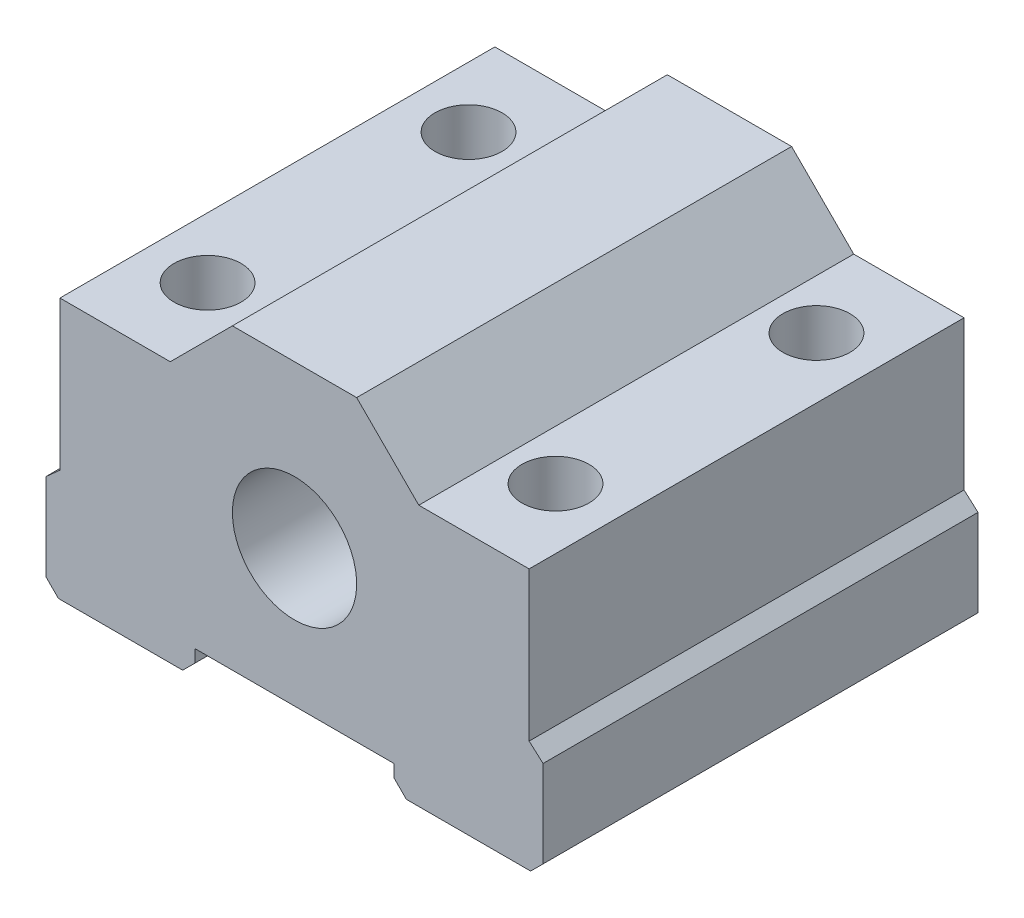
SolidWorks part; units mm, degrees
ref_plane "Спереди" through (0, 0, 0) normal (0, 0, 1) x (1, 0, 0)
ref_plane "Сверху" through (0, 0, 0) normal (0, 1, 0) x (1, 0, 0)
ref_plane "Справа" through (0, 0, 0) normal (1, 0, 0) x (0, 0, -1)
sketch "Эскиз1" plane through (0, 0, 0) normal (0, 0, 1) x (1, 0, 0)
  line L1 (-20, 13) -> (20, 13)
  line L2 (-20, 13) -> (-20, -13)
  line L3 (-20, -13) -> (20, -13)
  line L4 (20, 13) -> (20, -13)
  line L5 (-20, 13) -> (20, -13) construction
  line L6 (-20, -13) -> (20, 13) construction
  point P0 (0, 0)
  dimension "D1" = 26
  dimension "D2" = 40
extrude "Бобышка-Вытянуть1" add sketch "Эскиз1" along normal blind 35
sketch "Эскиз2" plane through (0, 0, 0) normal (0, 0, -1) x (-1, 0, 0)
  line L0 (-20, -13) -> (-20, 8)
  line L1 (-20, -13) -> (-20, 13) construction
  line L2 (0, 43.1229) -> (0, -17.1229) construction
  line L3 (-20, 8) -> (-10, 8)
  line L4 (-10, 8) -> (-5, 13)
  line L5 (-20, 13) -> (20, 13) construction
  line L6 (-5, 13) -> (5, 13)
  line L7 (5, 13) -> (10, 8)
  line L8 (10, 8) -> (20, 8)
  line L9 (20, 13) -> (20, -13) construction
  line L10 (0, -13) -> (0, 0)
  line L11 (20, -13) -> (-20, -13) construction
  circle A0 centre (0, 0) radius 5
  circle A1 centre (0, 0) radius 10
  point P8 (0, 13)
  line M9 (-20, 13) -> (-20, -13)
  line M11 (20, -13) -> (20, 13)
  line M12 (20, 13) -> (-20, 13)
  dimension "D4" = 10
  dimension "D5" = 20
  dimension "D1" = 21
  dimension "D2" = 10
  dimension "D3" = 13
extrude "Вырез-Вытянуть1" cut sketch "Эскиз2" against normal through all contours L3 L4 M12 M9 | L7 L8 M11 M12 | A0 L2 L10 | L2 A0 L10
sketch "Эскиз4" plane through (0, 8, 0) normal (0, 1, 0) x (1, 0, 0)
  line L0 (-20, -7) -> (-20, -28)
  line L1 (-20, -35) -> (-20, 0) construction
  line L2 (-20, -7) -> (-10, -7)
  line L3 (-10, -35) -> (-10, 0) construction
  line L4 (-20, -28) -> (-10, -28)
  line L5 (0, 0) -> (0, -35) construction
  line L6 (5, -35) -> (-5, -35) construction
  circle A0 centre (-15, -7) radius 2.5
  circle A1 centre (-15, -28) radius 2.5
  circle A2 centre (15, -28) radius 2.5
  circle A3 centre (15, -7) radius 2.5
  point P4 (-20, -17.5)
  point P5 (-20, -17.5)
  dimension "D2" = 5
  dimension "D3" = 5
  dimension "D1" = 21
extrude "Вырез-Вытянуть2" cut sketch "Эскиз4" against normal through all contours L2 A0 | L2 A0 | L4 A1 | L4 A1 | A2 | A3
sketch "Эскиз6" plane through (0, 0, 35) normal (0, 0, 1) x (1, 0, 0)
  line L0 (-20, 8) -> (-18.8782, 8)
  line L1 (-10, 8) -> (-20, 8) construction
  line L2 (-18.8782, 8) -> (-18.8782, -4)
  line L3 (-18.8782, -4) -> (-20, -5)
  line L4 (-20, 8) -> (-20, -13) construction
  line L5 (-20, -5) -> (-20, -13)
  line L6 (-20, -5) -> (-20, 8)
  line L7 (0, 13) -> (0, -13.546) construction
  line L8 (5, 13) -> (-5, 13) construction
  line L9 (18.8782, -4) -> (20, -5)
  line L10 (20, -5) -> (20, -13)
  line L11 (20, 8) -> (18.8782, 8)
  line L12 (18.8782, 8) -> (18.8782, -4)
  line L13 (20, -5) -> (20, 8)
  line M9 (-10, 8) -> (-20, 8)
  line M10 (-20, 8) -> (-20, -13)
  line M12 (20, -13) -> (20, 8)
  line M13 (20, 8) -> (10, 8)
  dimension "D1" = 8
  dimension "D2" = 9
extrude "Вырез-Вытянуть3" cut sketch "Эскиз6" against normal through all contours L3 L2 M9 M10 | L12 L9 M13 M12
sketch "Эскиз7" plane through (0, 0, 35) normal (0, 0, 1) x (1, 0, 0)
  line L0 (-20, -13) -> (-8, -13)
  line L1 (-20, -13) -> (20, -13) construction
  line L2 (-8, -13) -> (-8, -11)
  line L3 (-8, -11) -> (8, -11)
  line L4 (8, -11) -> (8, -13)
  line L5 (8, -13) -> (20, -13)
  line L6 (0, 13.7447) -> (0, -15.4007) construction
  line L7 (-8, -13) -> (8, -13)
  point P12 (1.3579, -10.4989)
  point P13 (0, 0)
  line M17 (-20, -13) -> (20, -13)
  dimension "D1" = 12
  dimension "D2" = 2
extrude "Вырез-Вытянуть4" cut sketch "Эскиз7" against normal through all contours L6 L3 L2 M17 | L3 L6 L7 L4
chamfer "Фаска1" distance 1 angle 45 4 edges at (20, -13, 17.5) (8, -13, 17.5) (-8, -13, 17.5) (-20, -13, 17.5)
sketch "Эскиз9" plane through (0, -13, 0) normal (0, -1, 0) x (1, 0, 0)
  circle A0 centre (-15, 28) radius 2.5
extrude "Бобышка-Вытянуть2" add sketch "Эскиз9" against normal up to surface (21 mm away) up to face at (-17.5, 8, 7)
sketch "Эскиз10" plane through (0, -13, 0) normal (0, -1, 0) x (1, 0, 0)
  line L0 (15, 28) -> (-15, 28)
  line L1 (0, 28) -> (-14, 28)
  line L2 (0, 28) -> (0, 19.9261)
  circle A0 centre (-14, 28) radius 2.7
  dimension "D3" = 5.4
  dimension "D1" = 30
  dimension "D2" = 14
extrude "Вырез-Вытянуть5" cut sketch "Эскиз10" against normal through all
sketch "Эскиз13" plane through (0, -13, 0) normal (0, -1, 0) x (1, 0, 0)
  circle A0 centre (-15, 7) radius 2.5
  circle A1 centre (15, 7) radius 2.5
  circle A2 centre (15, 28) radius 2.5
extrude "Бобышка-Вытянуть3" add sketch "Эскиз13" against normal up to surface (21 mm away) up to face at (12.5, 8, 7)
sketch "Эскиз14" plane through (0, -13, 0) normal (0, -1, 0) x (1, 0, 0)
  line L0 (-14, 28) -> (14, 28)
  line L1 (14, 28) -> (0, 28)
  circle A0 centre (-14, 28) radius 2.7
  circle A1 centre (14, 28) radius 2.7
  dimension "D1" = 28
extrude "Вырез-Вытянуть6" cut sketch "Эскиз14" against normal through all
sketch "Эскиз15" plane through (0, -13, 0) normal (0, -1, 0) x (1, 0, 0)
  line L0 (-14, 28) -> (-14, 7)
  line L1 (0, 0) -> (0, 35)
  line L2 (-8, 35) -> (8, 35) construction
  circle A0 centre (-14, 7) radius 2.7
  circle A1 centre (14, 7) radius 2.7
  dimension "D2" = 5.4
  dimension "D1" = 21
extrude "Вырез-Вытянуть7" cut sketch "Эскиз15" against normal through all
